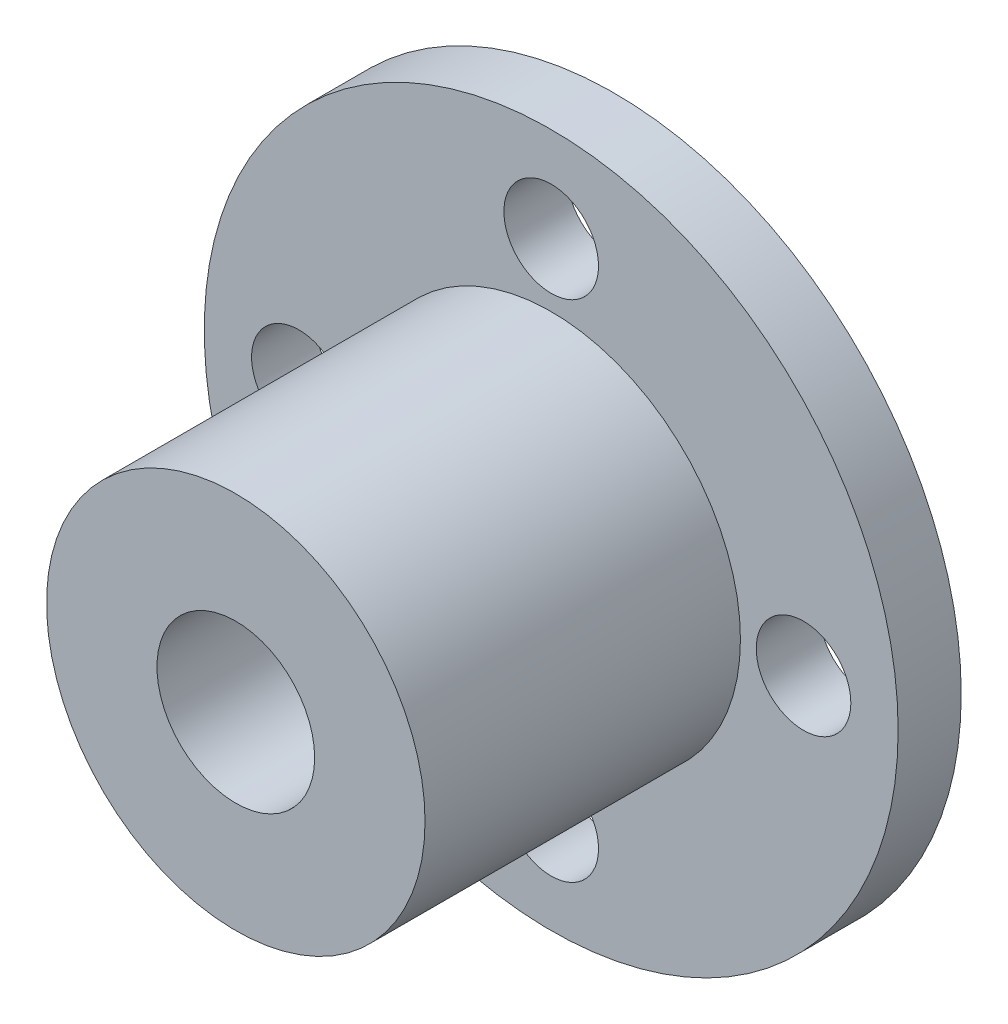
SolidWorks part; units mm, degrees
ref_plane "Front Plane" through (0, 0, 0) normal (0, 0, 1) x (1, 0, 0)
ref_plane "Top Plane" through (0, 0, 0) normal (0, 1, 0) x (1, 0, 0)
ref_plane "Right Plane" through (0, 0, 0) normal (1, 0, 0) x (0, 0, -1)
sketch "Sketch1" plane through (0, 0, 0) normal (0, 0, 1) x (1, 0, 0)
  circle A0 centre (0, 0) radius 11
extrude "Boss-Extrude1" add sketch "Sketch1" along normal blind 2
sketch "Sketch2" plane through (0, 0, 2) normal (0, 0, 1) x (1, 0, 0)
  circle A0 centre (0, 0) radius 6
extrude "Boss-Extrude2" add sketch "Sketch2" along normal blind 10
sketch "Sketch3" plane through (0, 0, 12) normal (0, 0, 1) x (1, 0, 0)
  circle A0 centre (0, 0) radius 2.5
extrude "Cut-Extrude1" cut sketch "Sketch3" against normal through all
sketch "Sketch5" plane through (0, 0, 2) normal (0, 0, 1) x (1, 0, 0)
  circle A0 centre (0, 0) radius 8 construction
  circle A1 centre (0, 8) radius 1.5
  circle A2 centre (8, 0) radius 1.5
  circle A3 centre (0, -8) radius 1.5
  circle A4 centre (-8, 0) radius 1.5
extrude "Cut-Extrude2" cut sketch "Sketch5" against normal through all
